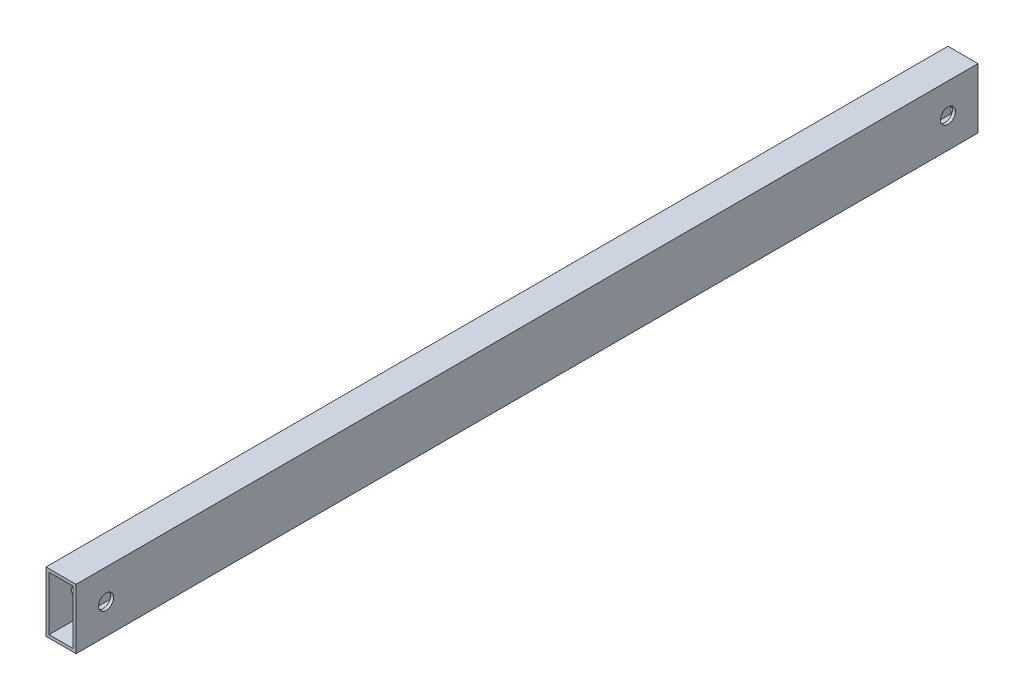
SolidWorks part; units mm, degrees
ref_plane "Front Plane" through (0, 0, 0) normal (0, 0, 1) x (1, 0, 0)
ref_plane "Top Plane" through (0, 0, 0) normal (0, 1, 0) x (1, 0, 0)
ref_plane "Right Plane" through (0, 0, 0) normal (1, 0, 0) x (0, 0, -1)
sketch "Sketch1" plane through (0, 0, 0) normal (0, 0, 1) x (1, 0, 0)
  line L0 (-4, -9) -> (4, -9)
  line L1 (-5, -10) -> (5, -10)
  line L2 (-5, -10) -> (-5, 10)
  line L3 (-5, 10) -> (5, 10)
  line L4 (5, -10) -> (5, 10)
  line L5 (-5, -10) -> (5, 10) construction
  line L6 (-5, 10) -> (5, -10) construction
  line L7 (4, -9) -> (4, 9)
  line L8 (-4, 9) -> (4, 9)
  line L9 (-4, -9) -> (-4, 9)
  point P0 (0, 0)
  dimension "D2" = 10
  dimension "D3" = 20
  dimension "D1" = 1
extrude "Boss-Extrude1" add sketch "Sketch1" along normal blind 300
sketch "Sketch2" plane through (5, 0, 0) normal (1, 0, 0) x (0, 0, -1)
  line L0 (0, 0) -> (-300, 0) construction
  line L1 (-300, -10) -> (-300, 10) construction
  circle A0 centre (-10, 0) radius 2.5
  circle A1 centre (-290, 0) radius 2.5
  dimension "D1" = 5
  dimension "D2" = 280
  dimension "D3" = 10
extrude "Cut-Extrude1" cut sketch "Sketch2" against normal through all
